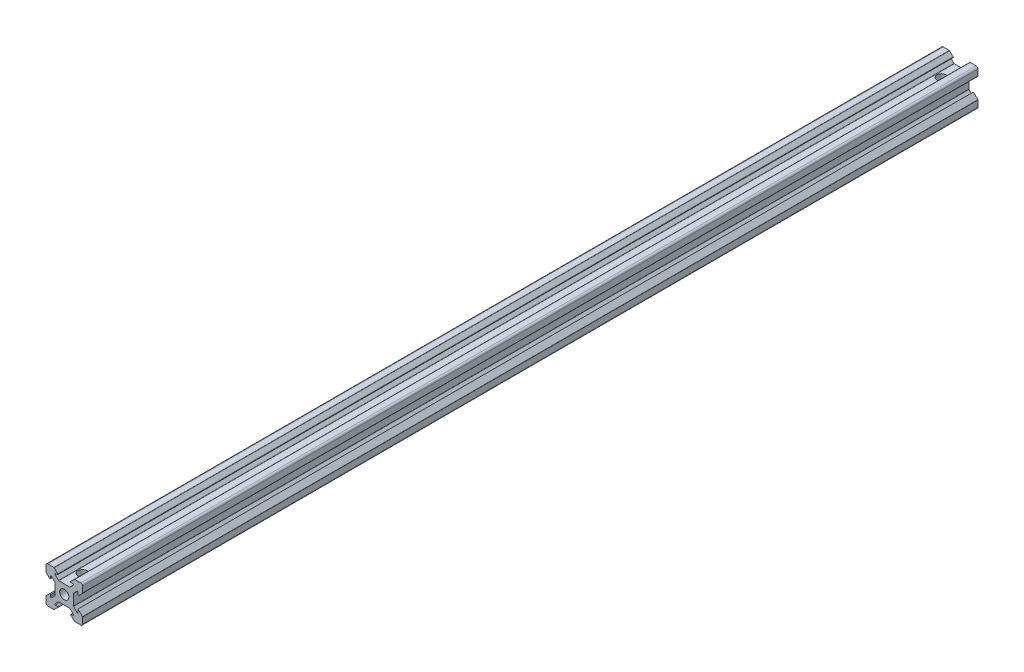
SolidWorks part; units mm, degrees
ref_plane "Alzado" through (0, 0, 0) normal (0, 0, 1) x (1, 0, 0)
ref_plane "Planta" through (0, 0, 0) normal (0, 1, 0) x (1, 0, 0)
ref_plane "Vista lateral" through (0, 0, 0) normal (1, 0, 0) x (0, 0, -1)
sketch "Croquis1" plane through (0, 0, 0) normal (0, 1, 0) x (1, 0, 0)
  line L0 (0, 245) -> (0, -245)
  dimension "D1" = 490
other "Miembro estructural1"
ref_plane "Plano1" through (0, 0, -245) normal (0, 0, 1) x (1, 0, 0)
sketch "Croquis11" plane through (0, 0, -245) normal (0, 0, 1) x (1, 0, 0)
  line L0 (0, 10) -> (0, -10) construction
  line L1 (-9, -10) -> (-5.714, -10)
  line L2 (-10, -9) -> (-10, -5.714)
  line L3 (-9, 10) -> (-5.714, 10)
  line L4 (10, -9) -> (10, -5.714)
  line L5 (-10, -10) -> (10, 10) construction
  line L6 (-10, 10) -> (10, -10) construction
  line L7 (-10, 0) -> (10, 0) construction
  line L8 (-5.5019, 9.9121) -> (-3.6121, 8.0224)
  line L9 (-3.8243, 7.5103) -> (-4.8471, 7.5103)
  line L10 (-5.0593, 6.9981) -> (-3.1695, 5.1084)
  line L11 (-2.9574, 5.0205) -> (2.9574, 5.0205)
  line L12 (3.1, 7.5103) -> (4.8471, 7.5103)
  line L13 (5.0593, 6.9981) -> (3.1695, 5.1084)
  line L14 (5.5019, 9.9121) -> (3.1, 7.5103)
  line L15 (5.714, 10) -> (9, 10)
  line L16 (9.9121, 5.5019) -> (8.0224, 3.6121)
  line L17 (7.5103, 3.8243) -> (7.5103, 4.8471)
  line L18 (6.9981, 5.0593) -> (5.1084, 3.1695)
  line L19 (5.0205, 2.9574) -> (5.0205, -2.9574)
  line L20 (6.9981, -5.0593) -> (5.1084, -3.1695)
  line L21 (7.5103, -3.1) -> (7.5103, -4.8471)
  line L22 (9.9121, -5.5019) -> (7.5103, -3.1)
  line L23 (5.5019, -9.9121) -> (3.6121, -8.0224)
  line L24 (3.8243, -7.5103) -> (4.8471, -7.5103)
  line L25 (5.0593, -6.9981) -> (3.1695, -5.1084)
  line L26 (2.9574, -5.0205) -> (-2.9574, -5.0205)
  line L27 (-5.0593, -6.9981) -> (-3.1695, -5.1084)
  line L28 (-3.8243, -7.5103) -> (-4.8471, -7.5103)
  line L29 (-5.5019, -9.9121) -> (-3.6121, -8.0224)
  line L30 (-9.9121, -5.5019) -> (-8.0224, -3.6121)
  line L31 (-7.5103, -3.8243) -> (-7.5103, -4.8471)
  line L32 (-6.9981, -5.0593) -> (-5.1084, -3.1695)
  line L33 (-5.0205, -2.9574) -> (-5.0205, 2.9574)
  line L34 (-6.9981, 5.0593) -> (-5.1084, 3.1695)
  line L35 (-7.5103, 3.8243) -> (-7.5103, 4.8471)
  line L36 (-9.9121, 5.5019) -> (-8.0224, 3.6121)
  line L37 (-10, 5.714) -> (-10, 9)
  line L38 (10, 5.714) -> (10, 9)
  line L39 (5.714, -10) -> (9, -10)
  circle A0 centre (0, 0) radius 2.5
  arc A1 (5.5019, 9.9121) -> (5.714, 10) centre (5.714, 9.7) cw
  arc A2 (9.9121, 5.5019) -> (10, 5.714) centre (9.7, 5.714) ccw
  arc A3 (9.9121, -5.5019) -> (10, -5.714) centre (9.7, -5.714) cw
  arc A4 (5.5019, -9.9121) -> (5.714, -10) centre (5.714, -9.7) ccw
  arc A5 (-5.5019, -9.9121) -> (-5.714, -10) centre (-5.714, -9.7) cw
  arc A6 (-9.9121, -5.5019) -> (-10, -5.714) centre (-9.7, -5.714) ccw
  arc A7 (-5.5019, 9.9121) -> (-5.714, 10) centre (-5.714, 9.7) ccw
  arc A8 (-3.6121, 8.0224) -> (-3.8243, 7.5103) centre (-3.8243, 7.8103) cw
  arc A9 (-4.8471, 7.5103) -> (-5.0593, 6.9981) centre (-4.8471, 7.2103) ccw
  arc A10 (-3.1695, 5.1084) -> (-2.9574, 5.0205) centre (-2.9574, 5.3205) ccw
  arc A11 (3.1695, 5.1084) -> (2.9574, 5.0205) centre (2.9574, 5.3205) cw
  arc A12 (4.8471, 7.5103) -> (5.0593, 6.9981) centre (4.8471, 7.2103) cw
  arc A13 (8.0224, 3.6121) -> (7.5103, 3.8243) centre (7.8103, 3.8243) cw
  arc A14 (7.5103, 4.8471) -> (6.9981, 5.0593) centre (7.2103, 4.8471) ccw
  arc A15 (5.1084, 3.1695) -> (5.0205, 2.9574) centre (5.3205, 2.9574) ccw
  arc A16 (5.0205, -2.9574) -> (5.1084, -3.1695) centre (5.3205, -2.9574) ccw
  arc A17 (6.9981, -5.0593) -> (7.5103, -4.8471) centre (7.2103, -4.8471) ccw
  arc A18 (3.6121, -8.0224) -> (3.8243, -7.5103) centre (3.8243, -7.8103) cw
  arc A19 (4.8471, -7.5103) -> (5.0593, -6.9981) centre (4.8471, -7.2103) ccw
  arc A20 (3.1695, -5.1084) -> (2.9574, -5.0205) centre (2.9574, -5.3205) ccw
  arc A21 (-3.8243, -7.5103) -> (-3.6121, -8.0224) centre (-3.8243, -7.8103) cw
  arc A22 (-2.9574, -5.0205) -> (-3.1695, -5.1084) centre (-2.9574, -5.3205) ccw
  arc A23 (-5.0593, -6.9981) -> (-4.8471, -7.5103) centre (-4.8471, -7.2103) ccw
  arc A24 (-8.0224, -3.6121) -> (-7.5103, -3.8243) centre (-7.8103, -3.8243) cw
  arc A25 (-7.5103, -4.8471) -> (-6.9981, -5.0593) centre (-7.2103, -4.8471) ccw
  arc A26 (-5.1084, -3.1695) -> (-5.0205, -2.9574) centre (-5.3205, -2.9574) ccw
  arc A27 (-5.0205, 2.9574) -> (-5.1084, 3.1695) centre (-5.3205, 2.9574) ccw
  arc A28 (-6.9981, 5.0593) -> (-7.5103, 4.8471) centre (-7.2103, 4.8471) ccw
  arc A29 (-7.5103, 3.8243) -> (-8.0224, 3.6121) centre (-7.8103, 3.8243) cw
  arc A30 (-9.9121, 5.5019) -> (-10, 5.714) centre (-9.7, 5.714) cw
  arc A31 (-9, -10) -> (-10, -9) centre (-9, -9) cw
  arc A32 (9, -10) -> (10, -9) centre (9, -9) ccw
  arc A33 (9, 10) -> (10, 9) centre (9, 9) cw
  arc A34 (-10, 9) -> (-9, 10) centre (-9, 9) cw
  point P0 (0, 0)
  point P18 (0, 5.0205)
  point P23 (5.5897, 10)
  point P48 (0, 0)
  point P61 (-5.5897, 10)
  point P64 (-3.1, 7.5103)
  point P67 (-5.5714, 7.5103)
  point P70 (-3.0817, 5.0205)
  point P73 (3.0817, 5.0205)
  point P76 (5.5714, 7.5103)
  point P125 (0, 0)
  dimension "D3" = 5
  dimension "D7" = 0.3
  dimension "D8" = 1
  dimension "D1" = 20
  dimension "D2" = 20
  dimension "D4" = 3.1
  dimension "D5" = 45
  dimension "D6" = 4
sketch "Croquis12" plane through (0, 5.0205, 0) normal (0, 1, 0) x (1, 0, 0)
  line L0 (0, 245) -> (0, 235) construction
  line L1 (0, 245) -> (0, -245) construction
  line L2 (0, 0) -> (66.3045, 0) construction
  circle A0 centre (0, 235) radius 2.5
  circle A1 centre (0, -235) radius 2.5
  dimension "D2" = 5
  dimension "D1" = 10
extrude "Cortar-Extruir1" cut sketch "Croquis12" against normal blind 12
